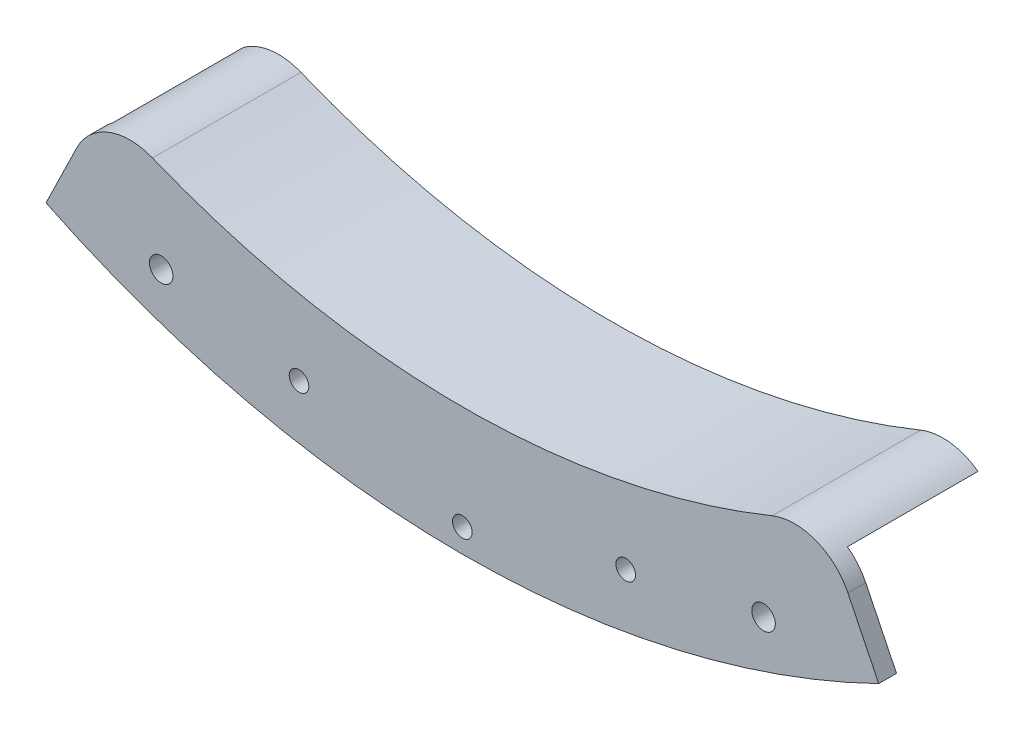
SolidWorks part; units mm, degrees
material "PLA"
ref_plane "前视基准面" through (0, 0, 0) normal (0, 0, 1) x (1, 0, 0)
ref_plane "上视基准面" through (0, 0, 0) normal (0, 1, 0) x (1, 0, 0)
ref_plane "右视基准面" through (0, 0, 0) normal (1, 0, 0) x (0, 0, -1)
sketch "草图1" plane through (0, 0, 0) normal (0, 0, 1) x (1, 0, 0)
  line L0 (0, 226.0354) -> (0, -266.8065) construction
  line L1 (0, 0) -> (-62.9063, -128.9769)
  line L2 (0, 0) -> (62.9063, -128.9769)
  circle A0 centre (0, 0) radius 138.5
  circle A1 centre (0, 0) radius 143.5
  dimension "D1" = 277
  dimension "D2" = 287
  dimension "D3" = 26
extrude "凸台-拉伸1" add sketch "草图1" along normal blind 25 contours A0 L0 A1 L2 | L0 A0 L1 A1
sketch "草图2" plane through (0, 0, 25) normal (0, 0, 1) x (1, 0, 0)
  line L0 (0, 0) -> (70.1394, -143.807)
  line L1 (0, 0) -> (-70.1394, -143.807)
  line L2 (-60.7144, -124.483) -> (-62.9063, -128.9769) construction
  line L3 (60.7144, -124.483) -> (62.9063, -128.9769) construction
  circle A0 centre (0, 0) radius 160
  arc M6 (-62.9063, -128.9769) -> (62.9063, -128.9769) centre (0, 0) ccw
  dimension "D1" = 320
extrude "凸台-拉伸2" add sketch "草图2" against normal blind 3 contours L1 A0 L0 M6
sketch "草图3" plane through (0, 0, 22) normal (0, 0, -1) x (-1, 0, 0)
  line L0 (0, 0) -> (0, -162.5) construction
  line L1 (0, 0) -> (-16.4216, -161.6681)
  line L2 (0, 0) -> (-22.6156, -160.9186)
  line L3 (0, 0) -> (16.4216, -161.6681)
  line L4 (0, 0) -> (22.6156, -160.9186)
  line L5 (0, 0) -> (-29.6133, -159.7789) construction
  circle A0 centre (0, 0) radius 143.5
  circle A1 centre (0, 0) radius 162.5
  circle A2 centre (0, -156) radius 1.65
  circle A3 centre (0, 0) radius 151 construction
  circle A4 centre (-27.5176, -148.4715) radius 1.65
  circle A5 centre (27.5176, -148.4715) radius 1.65
  arc M9 (62.9063, -128.9769) -> (-62.9063, -128.9769) centre (0, 0) cw
  arc M11 (-70.1394, -143.807) -> (70.1394, -143.807) centre (0, 0) ccw
  dimension "D1" = 5.8
  dimension "D3" = 3.3
  dimension "D5" = 302
  dimension "D7" = 3.3
  dimension "D2" = 8
  dimension "D4" = 156
  dimension "D6" = 10.5
extrude "凸台-拉伸3" add sketch "草图3" along normal blind 22 contours A4 | A2 | L2 L1 M9 M11 | L4 L3 M9 M11 | A5
sketch "草图4" plane through (0, 0, 0) normal (0, 0, -1) x (-1, 0, 0)
  circle A0 centre (-27.5176, -148.4715) radius 1.65
  circle A1 centre (0, -156) radius 1.65
  circle A2 centre (27.5176, -148.4715) radius 1.65
  dimension "D1" = 3.3
  dimension "D2" = 3.3
  dimension "D3" = 3.3
extrude "切除-拉伸1" cut sketch "草图4" against normal through all
sketch "草图6" plane through (0, 0, 0) normal (0.9903, 0.1392, 0) x (0, 0, -1)
  line L0 (0, -143.5) -> (-22, -160)
  line L1 (-22, -160) -> (0, -160)
  line L2 (0, -160) -> (0, -143.5)
revolve "切除-旋转1" cut sketch "草图6" angle 360 about axis through (0, 0, 25) along (0, 0, -1)
fillet "圆角1" radius 10 2 edges at (60.7144, -124.483, 12.5) (-60.7144, -124.483, 12.5)
sketch "草图7" plane through (0, 0, 22) normal (0, 0, -1) x (-1, 0, 0)
  line L0 (0, -160) -> (0, -138.5) construction
  arc A0 (-16.169, -159.1809) -> (16.169, -159.1809) centre (0, 0) ccw construction
  arc A1 (-52.1939, -128.2889) -> (52.1939, -128.2889) centre (0, 0) ccw construction
  circle A2 centre (50.7369, -143.8124) radius 1.9846
  circle A3 centre (0, 0) radius 152.5 construction
  circle A4 centre (-50.7369, -143.8124) radius 1.9846
  dimension "D1" = 305
extrude "切除-拉伸2" cut sketch "草图7" against normal through all
